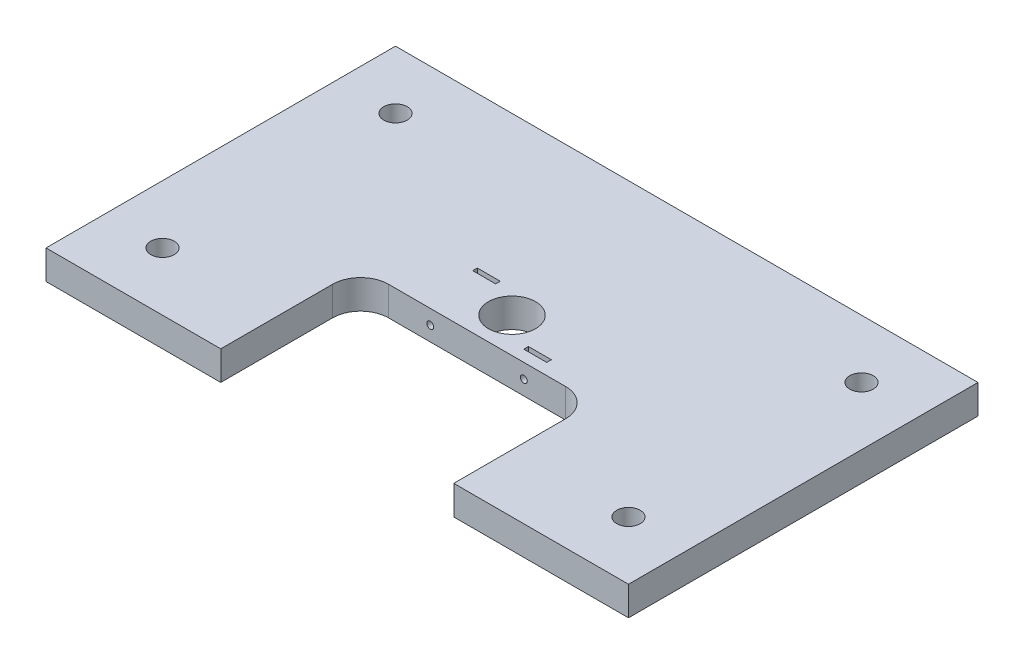
SolidWorks part; units mm, degrees
ref_plane "Front Plane" through (0, 0, 0) normal (0, 0, 1) x (1, 0, 0)
ref_plane "Top Plane" through (0, 0, 0) normal (0, 1, 0) x (1, 0, 0)
ref_plane "Right Plane" through (0, 0, 0) normal (1, 0, 0) x (0, 0, -1)
sketch "Sketch1" plane through (0, 0, 0) normal (0, 1, 0) x (1, 0, 0)
  line L1 (-63.5, -38.1) -> (63.5, -38.1)
  line L2 (-63.5, -38.1) -> (-63.5, 38.1)
  line L3 (-63.5, 38.1) -> (63.5, 38.1)
  line L4 (63.5, -38.1) -> (63.5, 38.1)
  line L5 (-63.5, -38.1) -> (63.5, 38.1) construction
  line L6 (-63.5, 38.1) -> (63.5, -38.1) construction
  point P0 (0, 0)
  dimension "D1" = 76.2
  dimension "D2" = 127
extrude "Boss-Extrude1" add sketch "Sketch1" along normal blind 6.35
sketch "Sketch3" plane through (0, 6.35, 0) normal (0, 1, 0) x (1, 0, 0)
  line L0 (25.4, -38.1) -> (25.4, -7.62)
  line L1 (-63.5, -38.1) -> (63.5, -38.1) construction
  line L2 (25.4, -7.62) -> (-25.4, -7.62)
  line L3 (-25.4, -7.62) -> (-25.4, -38.1)
  line L4 (-25.4, -38.1) -> (25.4, -38.1)
  line L5 (-63.5, 38.1) -> (-63.5, -38.1) construction
  line L7 (7.7, -4.125) -> (12.7, -4.125)
  line L8 (7.7, -4.125) -> (7.7, -5.125)
  line L9 (7.7, -5.125) -> (12.7, -5.125)
  line L10 (12.7, -4.125) -> (12.7, -5.125)
  line L11 (-12.7, 4.125) -> (-7.7, 4.125)
  line L12 (-12.7, 4.125) -> (-12.7, 5.125)
  line L13 (-12.7, 5.125) -> (-7.7, 5.125)
  line L14 (-7.7, 4.125) -> (-7.7, 5.125)
  circle A0 centre (0, 0) radius 5.125
  point P9 (0, -38.1)
  point P10 (0, -38.1)
  dimension "D3" = 10.25
  dimension "D1" = 38.1
  dimension "D2" = 30.48
  dimension "D4" = 5
  dimension "D5" = 1
  dimension "D6" = 12.7
  dimension "D7" = 12.7
extrude "Cut-Extrude1" cut sketch "Sketch3" against normal through all
fillet "Fillet1" radius 6.096 2 edges at (25.4, 3.175, 7.62) (-25.4, 3.175, 7.62)
sketch "Sketch4" plane through (0, 0, 7.62) normal (0, 0, 1) x (1, 0, 0)
  line L0 (19.304, 6.35) -> (-19.304, 6.35) construction
  line L1 (-7.7, 0) -> (-7.7, 6.35) construction
  line L2 (12.7, 0) -> (12.7, 6.35) construction
  circle A0 centre (-10.2, 3.175) radius 0.75
  circle A1 centre (10.2, 3.175) radius 0.75
  dimension "D1" = 1.5
  dimension "D2" = 3.175
  dimension "D3" = 2.5
  dimension "D4" = 2.5
extrude "Cut-Extrude2" cut sketch "Sketch4" against normal blind 19.05
hole_wizard "1/4-20 Tapped Hole1" positions "Sketch7" profile "Sketch8" tap size "1/4-20" standard "ANSI Inch" end condition through all
sketch "Sketch7" plane through (0, 6.35, 0) normal (0, 1, 0) x (1, 0, 0)
  line L0 (63.5, 38.1) -> (-63.5, 38.1) construction
  line L1 (-63.5, 38.1) -> (-63.5, -38.1) construction
  line L2 (63.5, -38.1) -> (63.5, 38.1) construction
  line L3 (25.4, -38.1) -> (63.5, -38.1) construction
  line L4 (-63.5, -38.1) -> (-25.4, -38.1) construction
  point P0 (-50.8, 25.4)
  point P2 (50.8, 25.4)
  point P4 (50.8, -25.4)
  point P6 (-50.8, -25.4)
  dimension "D1" = 12.7
  dimension "D2" = 12.7
  dimension "D3" = 12.7
  dimension "D4" = 12.7
  dimension "D5" = 12.7
  dimension "D6" = 12.7
  dimension "D7" = 12.7
  dimension "D8" = 12.7
sketch "Sketch8" plane through (-50.8, 6.35, -25.4) normal (1, 0, 0) x (0, 0, 1)
  line L0 (0, 0) -> (0, 6.35)
  line L1 (0, 6.35) -> (2.5527, 6.35)
  line L2 (2.5527, 6.35) -> (2.5527, 0)
  line L5 (2.5527, 0) -> (0, 0)
  line L11 (0, -6.35) -> (0, 107.95) construction
  dimension "Thru Tap Drill Dia." = 5.1054
  dimension "Thru Tap Drill Depth" = 6.35
cosmetic thread "Hole Thread2" parameters "D2"=6.35
cosmetic thread "Hole Thread3" parameters "D2"=6.35
cosmetic thread "Hole Thread4" parameters "D2"=6.35
cosmetic thread "Hole Thread5" parameters "D2"=6.35
